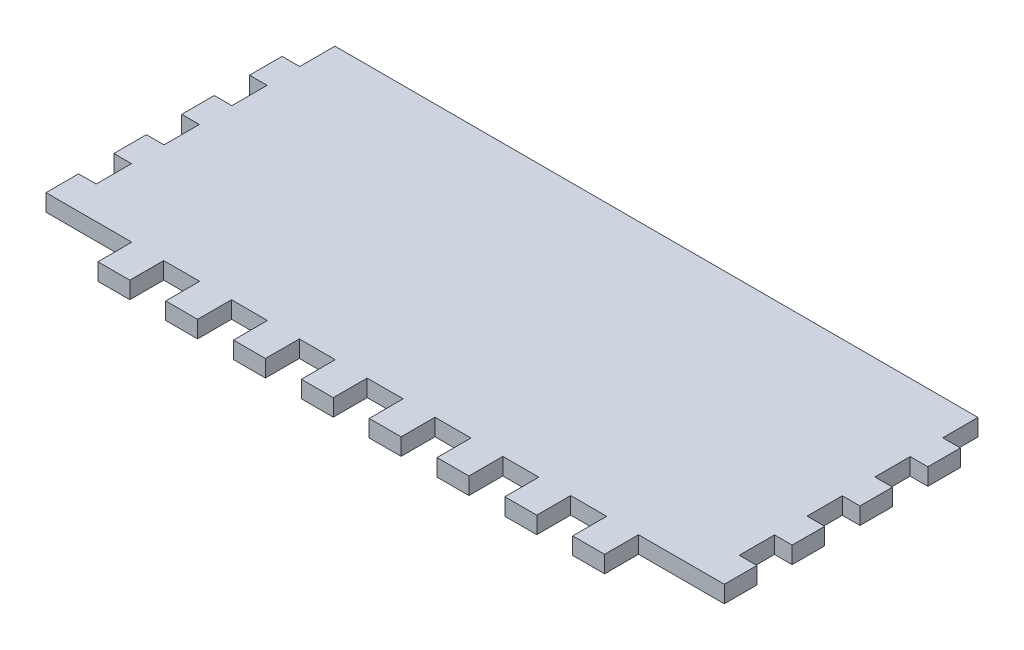
SolidWorks part; units mm, degrees
ref_plane "Front Plane" through (0, 0, 0) normal (0, 0, 1) x (1, 0, 0)
ref_plane "Top Plane" through (0, 0, 0) normal (0, 1, 0) x (1, 0, 0)
ref_plane "Right Plane" through (0, 0, 0) normal (1, 0, 0) x (0, 0, -1)
sketch "Sketch1" plane through (0, 0, 0) normal (0, 1, 0) x (1, 0, 0)
  line L1 (-63.5, -53.975) -> (63.5, -53.975)
  line L2 (-63.5, -53.975) -> (-63.5, 53.975)
  line L3 (-63.5, 53.975) -> (63.5, 53.975)
  line L4 (63.5, -53.975) -> (63.5, 53.975)
  line L5 (-63.5, -53.975) -> (63.5, 53.975) construction
  line L6 (-63.5, 53.975) -> (63.5, -53.975) construction
  point P0 (0, 0)
  dimension "D1" = 127
  dimension "D2" = 107.95
extrude "Boss-Extrude1" add sketch "Sketch1" along normal blind 3.175
sketch "Sketch2" plane through (0, 0, 0) normal (0, -1, 0) x (1, 0, 0)
  line L0 (-34.7345, 47.625) -> (-41.4655, 47.625)
  line L5 (63.5, 53.975) -> (63.5, -53.975) construction
  line L34 (0, 0) -> (0, -14.8721) construction
  line L39 (63.5, 41.529) -> (60.198, 41.529)
  line L41 (63.5, 54.229) -> (63.5, 47.625)
  line L42 (63.5, 47.625) -> (60.198, 47.625)
  line L44 (63.5, 41.529) -> (63.5, 34.925)
  line L45 (63.5, 34.925) -> (60.198, 34.925)
  line L46 (60.198, 41.529) -> (60.198, 34.925)
  line L47 (63.5, 28.829) -> (60.198, 28.829)
  line L48 (63.5, 28.829) -> (63.5, 22.225)
  line L49 (63.5, 22.225) -> (60.198, 22.225)
  line L50 (60.198, 28.829) -> (60.198, 22.225)
  line L51 (63.5, 16.129) -> (60.198, 16.129)
  line L52 (63.5, 16.129) -> (63.5, 9.525)
  line L53 (63.5, 9.525) -> (60.198, 9.525)
  line L54 (60.198, 16.129) -> (60.198, 9.525)
  line L55 (63.5, 3.429) -> (60.198, 3.429)
  line L56 (63.5, 3.429) -> (63.5, -3.175)
  line L57 (63.5, -3.175) -> (60.198, -3.175)
  line L58 (60.198, 3.429) -> (60.198, -3.175)
  line L59 (63.5, -9.271) -> (60.198, -9.271)
  line L60 (63.5, -9.271) -> (63.5, -15.875)
  line L61 (63.5, -15.875) -> (60.198, -15.875)
  line L62 (60.198, -9.271) -> (60.198, -15.875)
  line L63 (63.5, -21.971) -> (60.198, -21.971)
  line L64 (63.5, -21.971) -> (63.5, -28.575)
  line L65 (63.5, -28.575) -> (60.198, -28.575)
  line L66 (60.198, -21.971) -> (60.198, -28.575)
  line L67 (63.5, -34.671) -> (60.198, -34.671)
  line L68 (63.5, -34.671) -> (63.5, -41.275)
  line L69 (63.5, -41.275) -> (60.198, -41.275)
  line L70 (60.198, -34.671) -> (60.198, -41.275)
  line L71 (-60.198, -34.671) -> (-60.198, -41.275)
  line L72 (-63.5, -41.275) -> (-60.198, -41.275)
  line L73 (-63.5, -34.671) -> (-63.5, -41.275)
  line L74 (-63.5, -34.671) -> (-60.198, -34.671)
  line L75 (-60.198, -21.971) -> (-60.198, -28.575)
  line L76 (-63.5, -28.575) -> (-60.198, -28.575)
  line L77 (-63.5, -21.971) -> (-63.5, -28.575)
  line L78 (-63.5, -21.971) -> (-60.198, -21.971)
  line L79 (-60.198, -9.271) -> (-60.198, -15.875)
  line L80 (-63.5, -15.875) -> (-60.198, -15.875)
  line L81 (-63.5, -9.271) -> (-63.5, -15.875)
  line L82 (-63.5, -9.271) -> (-60.198, -9.271)
  line L83 (-60.198, 3.429) -> (-60.198, -3.175)
  line L84 (-63.5, -3.175) -> (-60.198, -3.175)
  line L85 (-63.5, 3.429) -> (-63.5, -3.175)
  line L86 (-63.5, 3.429) -> (-60.198, 3.429)
  line L87 (-60.198, 16.129) -> (-60.198, 9.525)
  line L88 (-63.5, 9.525) -> (-60.198, 9.525)
  line L89 (-63.5, 16.129) -> (-63.5, 9.525)
  line L90 (-63.5, 16.129) -> (-60.198, 16.129)
  line L91 (-60.198, 28.829) -> (-60.198, 22.225)
  line L92 (-63.5, 22.225) -> (-60.198, 22.225)
  line L93 (-63.5, 28.829) -> (-63.5, 22.225)
  line L94 (-63.5, 28.829) -> (-60.198, 28.829)
  line L95 (-60.198, 41.529) -> (-60.198, 34.925)
  line L96 (-63.5, 34.925) -> (-60.198, 34.925)
  line L97 (-63.5, 41.529) -> (-63.5, 34.925)
  line L99 (-63.5, 47.625) -> (-60.198, 47.625)
  line L100 (-63.5, 54.229) -> (-63.5, 47.625)
  line L102 (-63.5, 41.529) -> (-60.198, 41.529)
  line L103 (60.198, 47.625) -> (47.4345, 47.625)
  line L104 (34.7345, 47.625) -> (34.7345, 54.229)
  line L106 (34.7345, 54.229) -> (28.7655, 54.229)
  line L107 (28.7655, 54.229) -> (28.7655, 47.625)
  line L108 (28.7655, 47.625) -> (22.0345, 47.625)
  line L109 (22.0345, 47.625) -> (22.0345, 54.229)
  line L110 (22.0345, 54.229) -> (16.0655, 54.229)
  line L111 (16.0655, 54.229) -> (16.0655, 47.625)
  line L112 (16.0655, 47.625) -> (9.3345, 47.625)
  line L113 (9.3345, 47.625) -> (9.3345, 54.229)
  line L114 (9.3345, 54.229) -> (3.3655, 54.229)
  line L115 (3.3655, 54.229) -> (3.3655, 47.625)
  line L116 (3.3655, 47.625) -> (-3.3655, 47.625)
  line L117 (-3.3655, 47.625) -> (-3.3655, 54.229)
  line L118 (-3.3655, 54.229) -> (-9.3345, 54.229)
  line L119 (-9.3345, 54.229) -> (-9.3345, 47.625)
  line L120 (-9.3345, 47.625) -> (-16.0655, 47.625)
  line L121 (-16.0655, 47.625) -> (-16.0655, 54.229)
  line L122 (-16.0655, 54.229) -> (-22.0345, 54.229)
  line L123 (-22.0345, 54.229) -> (-22.0345, 47.625)
  line L124 (-22.0345, 47.625) -> (-28.7655, 47.625)
  line L125 (-28.7655, 47.625) -> (-28.7655, 54.229)
  line L126 (-28.7655, 54.229) -> (-34.7345, 54.229)
  line L127 (-34.7345, 54.229) -> (-34.7345, 47.625)
  line L137 (-63.5, 54.229) -> (-63.5, 63.0316)
  line L138 (63.5, -53.975) -> (-63.5, -53.975) construction
  line L139 (-63.5, 63.0316) -> (63.5, 63.0316)
  line L140 (63.5, 63.0316) -> (63.5, 54.229)
  line L141 (63.5, -47.371) -> (63.5, -53.975)
  line L142 (63.5, -53.975) -> (60.198, -53.975)
  line L143 (60.198, -53.975) -> (60.198, -47.371)
  line L144 (60.198, -47.371) -> (63.5, -47.371)
  line L145 (-60.198, -47.371) -> (-63.5, -47.371)
  line L146 (-60.198, -53.975) -> (-60.198, -47.371)
  line L147 (-63.5, -53.975) -> (-60.198, -53.975)
  line L148 (-63.5, -47.371) -> (-63.5, -53.975)
  line L149 (-63.5, -53.975) -> (-63.5, 53.975) construction
  line L150 (63.5, 53.975) -> (63.5, -53.975) construction
  line L151 (41.4655, 47.625) -> (41.4655, 54.229)
  line L152 (41.4655, 54.229) -> (47.4345, 54.229)
  line L153 (47.4345, 54.229) -> (47.4345, 47.625)
  line L154 (-41.4655, 47.625) -> (-41.4655, 54.229)
  line L155 (-41.4655, 54.229) -> (-47.4345, 54.229)
  line L156 (-47.4345, 54.229) -> (-47.4345, 47.625)
  line L157 (-47.4345, 47.625) -> (-60.198, 47.625)
  line L158 (41.4655, 47.625) -> (34.7345, 47.625)
  point P3 (0, 47.625)
  dimension "D2" = 6.604
  dimension "D3" = 5.969
  dimension "D6" = 6.731
  dimension "D8" = 3.302
  dimension "D9" = 9
extrude "Cut-Extrude1" cut sketch "Sketch2" against normal through all
sketch "Sketch3" plane through (0, 3.175, 0) normal (0, 1, 0) x (1, 0, 0)
  line L0 (60.198, 53.975) -> (-60.198, 53.975) construction
  line L1 (-63.5, 53.975) -> (63.5, 53.975)
  line L2 (-63.5, 53.975) -> (-63.5, 3.175)
  line L3 (-63.5, 3.175) -> (63.5, 3.175)
  line L4 (63.5, 53.975) -> (63.5, 3.175)
  line L5 (-63.5, 47.371) -> (-63.5, 41.275) construction
  line L6 (63.5, 41.275) -> (63.5, 47.371) construction
  line L7 (-63.5, -47.625) -> (-47.4345, -47.625) construction
  dimension "D1" = 50.8
extrude "Cut-Extrude2" cut sketch "Sketch3" against normal through all
